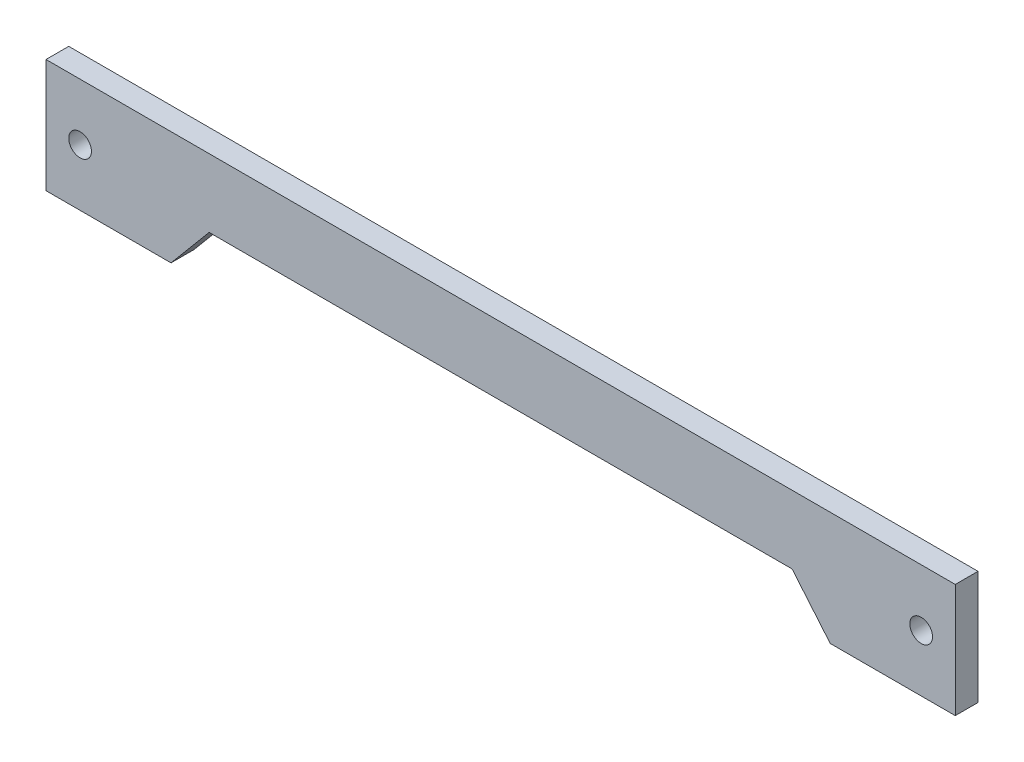
SolidWorks part; units mm, degrees
material "Pappelsperrholz"
ref_plane "Ebene vorne" through (0, 0, 0) normal (0, 0, 1) x (1, 0, 0)
ref_plane "Ebene oben" through (0, 0, 0) normal (0, 1, 0) x (1, 0, 0)
ref_plane "Ebene rechts" through (0, 0, 0) normal (1, 0, 0) x (0, 0, -1)
sketch "Skizze1" plane through (0, 0, 0) normal (0, 0, 1) x (1, 0, 0)
  line L0 (0, 0) -> (0, -22.0536) construction
  line L1 (80, 0) -> (-80, 0)
  line L2 (-80, 0) -> (-80, -20)
  line L3 (-80, -20) -> (-58, -20)
  line L4 (-58, -20) -> (-51.2872, -12)
  line L5 (-51.2872, -12) -> (51.2872, -12)
  line L6 (58, -20) -> (51.2872, -12)
  line L7 (80, -20) -> (58, -20)
  line L8 (80, 0) -> (80, -20)
  point P9 (0, -12)
  dimension "D1" = 160
  dimension "D2" = 20
  dimension "D3" = 12
  dimension "D4" = 22
  dimension "D5" = 130
extrude "Grundplatte" add sketch "Skizze1" along normal blind 4
sketch "Skizze2" plane through (0, 0, 4) normal (0, 0, 1) x (1, 0, 0)
  line L0 (0, 0) -> (0, -12) construction
  line L1 (-51.2872, -12) -> (51.2872, -12) construction
  line L2 (80, 0) -> (-80, 0) construction
  circle A0 centre (-74, -10) radius 2
  circle A1 centre (74, -10) radius 2
  dimension "D1" = 4
  dimension "D3" = 148
  dimension "D2" = 10
extrude "Schnitt-Linear austragen1" cut sketch "Skizze2" against normal through all
